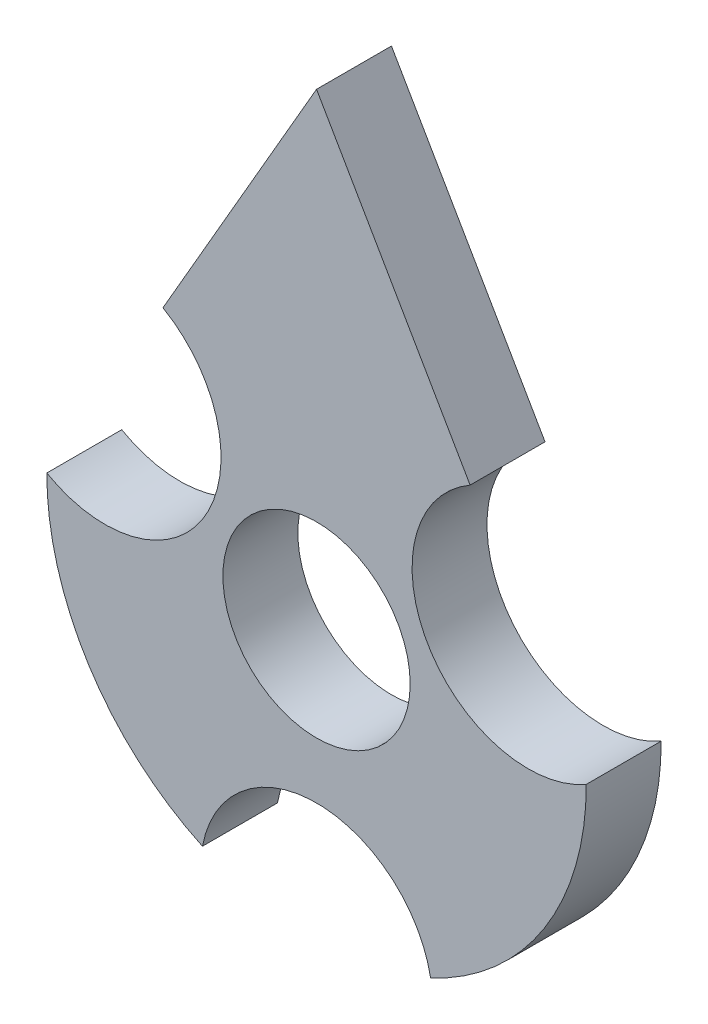
SolidWorks part; units mm, degrees
ref_plane "Front Plane" through (0, 0, 0) normal (0, 0, 1) x (1, 0, 0)
ref_plane "Top Plane" through (0, 0, 0) normal (0, 1, 0) x (1, 0, 0)
ref_plane "Right Plane" through (0, 0, 0) normal (1, 0, 0) x (0, 0, -1)
sketch "Sketch1" plane through (0, 0, 0) normal (0, 0, 1) x (1, 0, 0)
  line L0 (0, 0) -> (0, 32410.1394) construction
  line L1 (0, 0) -> (32410.1394, 0) construction
  line L2 (0, 125) -> (-41, 53.9859)
  line L3 (0, 125) -> (41, 53.9859)
  circle A2 centre (0, 0) radius 25
  arc A3 (30.4601, -65.2394) -> (71.9994, 0.292) centre (0, 0) ccw
  arc A4 (30.4601, -65.2394) -> (-30.4601, -65.2394) centre (0, -71) ccw
  arc A5 (-71.9994, 0.292) -> (-41, 53.9859) centre (-56.5, 27.1391) ccw
  arc A6 (71.9994, 0.292) -> (41, 53.9859) centre (56.5, 27.1391) cw
  arc A7 (-71.9994, 0.292) -> (-30.4601, -65.2394) centre (0, 0) ccw
  point P15 (0, 0)
  point P18 (0, 0)
  point P19 (0, 0)
  point P20 (-81.149, 46.3626)
  dimension "D1" = 50
  dimension "D2" = 144
  dimension "D5" = 60
  dimension "D8" = 125
  dimension "D3" = 62
  dimension "D4" = 62
  dimension "D6" = 113
  dimension "D7" = 196
extrude "Boss-Extrude1" add sketch "Sketch1" along normal mid plane 20
